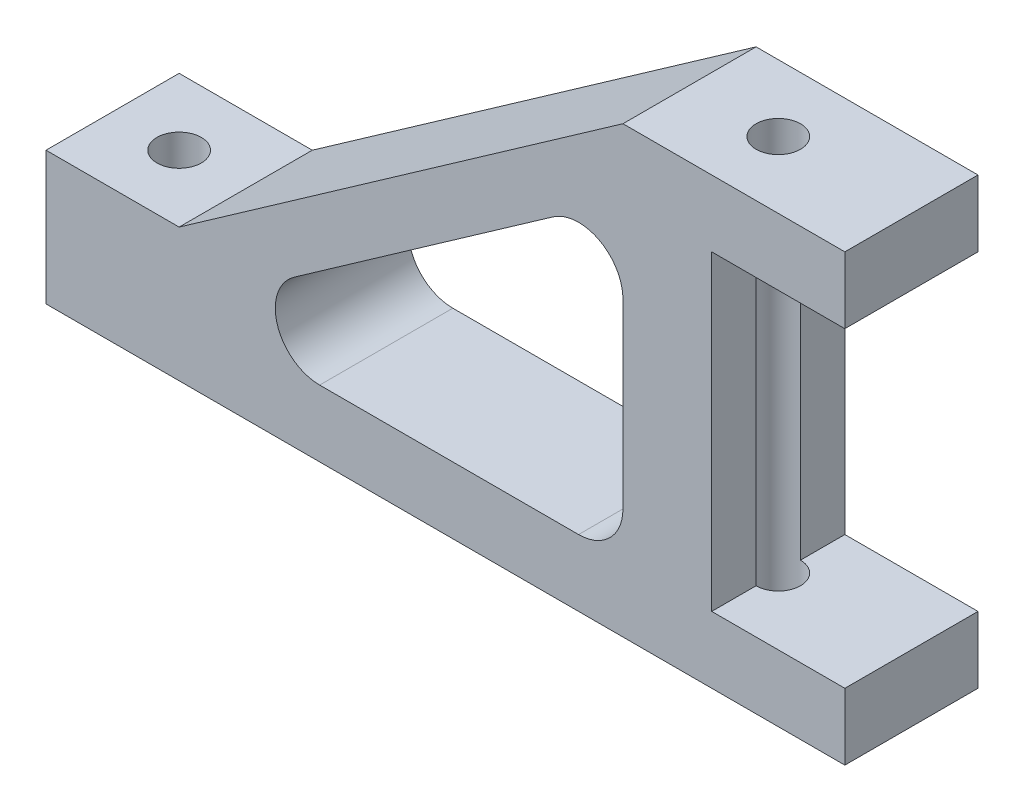
SolidWorks part; units mm, degrees
ref_plane "Front Plane" through (0, 0, 0) normal (0, 0, 1) x (1, 0, 0)
ref_plane "Top Plane" through (0, 0, 0) normal (0, 1, 0) x (1, 0, 0)
ref_plane "Right Plane" through (0, 0, 0) normal (1, 0, 0) x (0, 0, -1)
sketch "Sketch1" plane through (0, 0, 0) normal (0, 0, 1) x (1, 0, 0)
  line L0 (-77.5032, 15) -> (-77.5032, -15)
  line L1 (-77.5032, -15) -> (102.4968, -15)
  line L2 (102.4968, -15) -> (102.4968, 0)
  line L3 (102.4968, 0) -> (72.4968, 0)
  line L4 (72.4968, 0) -> (72.4968, 70.1656)
  line L5 (72.4968, 70.1656) -> (102.4968, 70.1656)
  line L6 (102.4968, 70.1656) -> (102.4968, 85.1656)
  line L7 (102.4968, 85.1656) -> (52.4968, 85.1656)
  line L9 (-77.5032, 15) -> (-47.5032, 15)
  line L10 (-47.5032, 15) -> (52.4968, 85.1656)
  line L11 (52.4968, 50.933) -> (52.4968, 10)
  line L12 (42.4968, 0) -> (-15.8409, 0)
  line L13 (-21.5846, 18.1859) -> (36.7531, 59.1189)
  arc A0 (52.4968, 10) -> (42.4968, 0) centre (42.4968, 10) cw
  arc A1 (-15.8409, 0) -> (-21.5846, 18.1859) centre (-15.8409, 10) cw
  arc A2 (52.4968, 50.933) -> (36.7531, 59.1189) centre (42.4968, 50.933) ccw
  dimension "D9" = 10
  dimension "D1" = 180
  dimension "D2" = 30
  dimension "D3" = 30
  dimension "D4" = 15
  dimension "D5" = 15
  dimension "D6" = 50
  dimension "D7" = 150
  dimension "D8" = 0
extrude "Boss-Extrude1" add sketch "Sketch1" along normal blind 30
sketch "Sketch2" plane through (0, 15, 0) normal (0, 1, 0) x (1, 0, 0)
  line L0 (-77.5032, -15) -> (102.4968, -15) construction
  line L1 (-77.5032, -30) -> (-77.5032, 0) construction
  line L2 (102.4968, -30) -> (102.4968, 0) construction
  line L3 (-62.5032, 0) -> (-62.5032, -30) construction
  line L4 (-47.5032, 0) -> (-77.5032, 0) construction
  line L5 (-47.5032, -30) -> (-77.5032, -30) construction
  circle A0 centre (-62.5032, -15) radius 5
  circle A1 centre (72.4968, -15) radius 5
  dimension "D1" = 10
  dimension "D2" = 10
  dimension "D3" = 135
extrude "Cut-Extrude1" cut sketch "Sketch2" against normal mid plane 180
